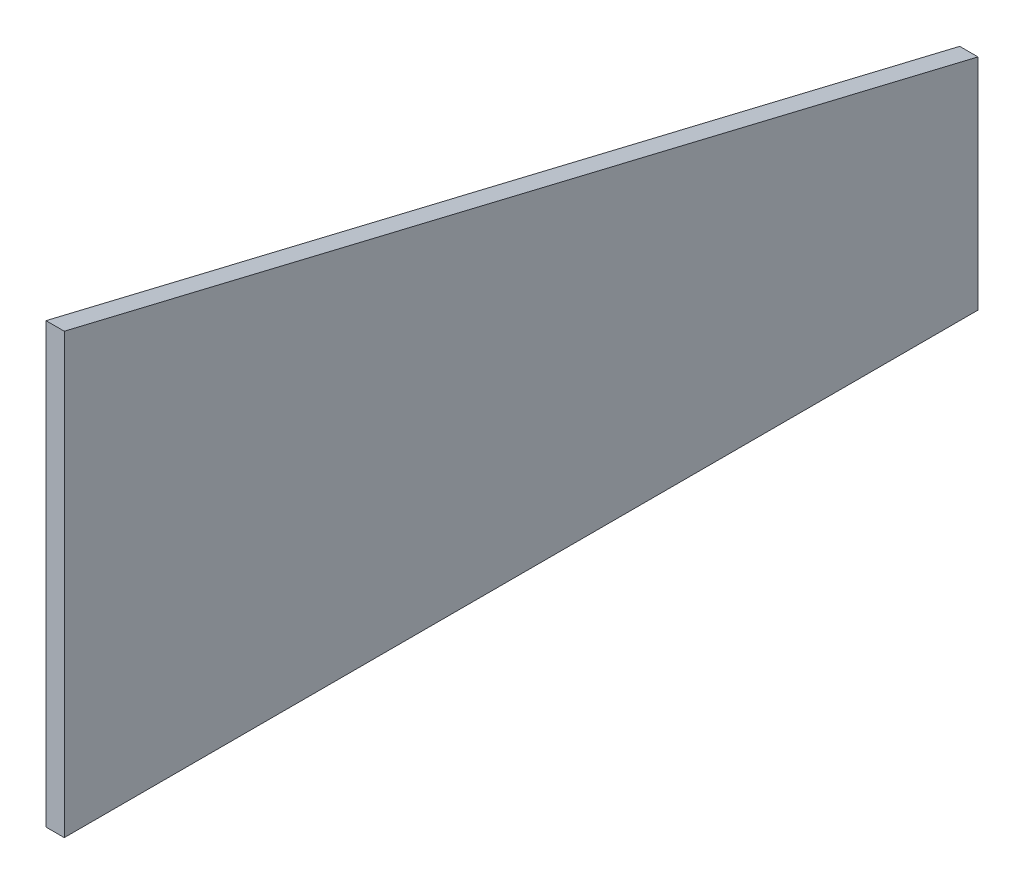
SolidWorks part; units mm, degrees
material "Pine"
ref_plane "Front Plane" through (0, 0, 0) normal (0, 0, 1) x (1, 0, 0)
ref_plane "Top Plane" through (0, 0, 0) normal (0, 1, 0) x (1, 0, 0)
ref_plane "Right Plane" through (0, 0, 0) normal (1, 0, 0) x (0, 0, -1)
sketch "Sketch1" plane through (0, 0, 0) normal (1, 0, 0) x (0, 0, -1)
  line L0 (0, 0) -> (317.5, 0)
  line L1 (317.5, 0) -> (317.5, 76.2)
  line L2 (0, 0) -> (0, 152.4)
  line L3 (0, 152.4) -> (317.5, 76.2)
extrude "Boss-Extrude1" add sketch "Sketch1" along normal blind 6.35
